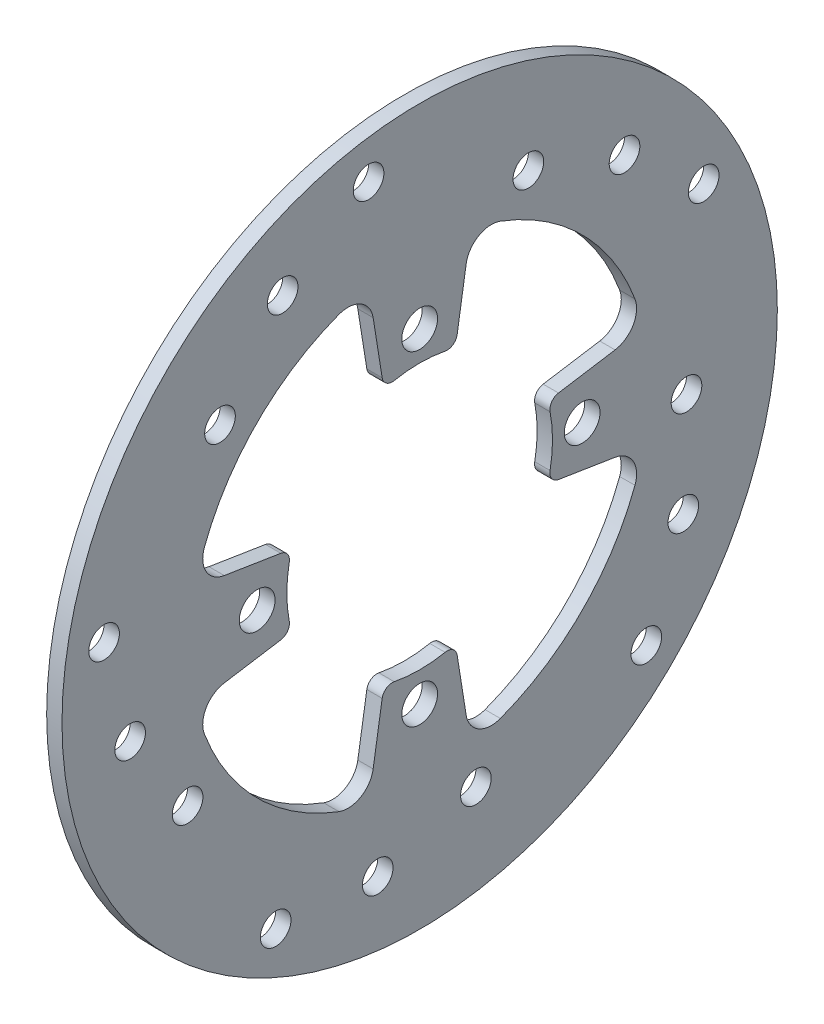
SolidWorks part; units mm, degrees
material "Stainless Steel (ferritic)"
ref_plane "Front Plane" through (0, 0, 0) normal (0, 0, 1) x (1, 0, 0)
ref_plane "Top Plane" through (0, 0, 0) normal (0, 1, 0) x (1, 0, 0)
ref_plane "Right Plane" through (0, 0, 0) normal (1, 0, 0) x (0, 0, -1)
sketch "Sketch1" plane through (0, 0, 0) normal (1, 0, 0) x (0, 0, -1)
  circle A0 centre (0, 0) radius 88.9
  dimension "D1" = 177.8
extrude "Boss-Extrude2" add sketch "Sketch1" along normal blind 3.81
sketch "Sketch3" plane through (3.81, 0, 0) normal (1, 0, 0) x (0, 0, -1)
  line L0 (0, 0) -> (0, 89.75) construction
  line L1 (9.3202, 34.5019) -> (11.5604, 48.5665)
  line L2 (34.5019, -9.3202) -> (48.5665, -11.5604)
  line L3 (-11.5604, 48.5665) -> (-9.3202, 34.5019)
  line L4 (48.5665, 11.5604) -> (34.5019, 9.3202)
  line L5 (-9.3202, -34.5019) -> (-11.5604, -48.5665)
  line L6 (11.5604, -48.5665) -> (9.3202, -34.5019)
  line L7 (-34.5019, 9.3202) -> (-48.5665, 11.5604)
  line L8 (-48.5665, -11.5604) -> (-34.5019, -9.3202)
  arc A0 (-20.0603, 53.5136) -> (-53.5136, 20.0603) centre (0, 0) ccw
  arc A1 (6.3253, 32.4085) -> (-6.3253, 32.4085) centre (0, 0) ccw
  arc A2 (9.3202, 34.5019) -> (6.3253, 32.4085) centre (6.8119, 34.9015) cw
  arc A3 (-9.3202, 34.5019) -> (-6.3253, 32.4085) centre (-6.8119, 34.9015) ccw
  arc A4 (11.5604, 48.5665) -> (20.0603, 53.5136) centre (17.8314, 47.5677) cw
  arc A5 (-20.0603, 53.5136) -> (-11.5604, 48.5665) centre (-17.8314, 47.5677) cw
  arc A6 (48.5665, -11.5604) -> (53.5136, -20.0603) centre (47.5677, -17.8314) cw
  arc A7 (34.5019, -9.3202) -> (32.4085, -6.3253) centre (34.9015, -6.8119) cw
  arc A8 (32.4085, -6.3253) -> (32.4085, 6.3253) centre (0, 0) ccw
  arc A9 (34.5019, 9.3202) -> (32.4085, 6.3253) centre (34.9015, 6.8119) ccw
  arc A10 (53.5136, 20.0603) -> (48.5665, 11.5604) centre (47.5677, 17.8314) cw
  arc A11 (-11.5604, -48.5665) -> (-20.0603, -53.5136) centre (-17.8314, -47.5677) cw
  arc A12 (-9.3202, -34.5019) -> (-6.3253, -32.4085) centre (-6.8119, -34.9015) cw
  arc A13 (-6.3253, -32.4085) -> (6.3253, -32.4085) centre (0, 0) ccw
  arc A14 (9.3202, -34.5019) -> (6.3253, -32.4085) centre (6.8119, -34.9015) ccw
  arc A15 (20.0603, -53.5136) -> (11.5604, -48.5665) centre (17.8314, -47.5677) cw
  arc A16 (-48.5665, 11.5604) -> (-53.5136, 20.0603) centre (-47.5677, 17.8314) cw
  arc A17 (-34.5019, 9.3202) -> (-32.4085, 6.3253) centre (-34.9015, 6.8119) cw
  arc A18 (-32.4085, 6.3253) -> (-32.4085, -6.3253) centre (0, 0) ccw
  arc A19 (-34.5019, -9.3202) -> (-32.4085, -6.3253) centre (-34.9015, -6.8119) ccw
  arc A20 (-53.5136, -20.0603) -> (-48.5665, -11.5604) centre (-47.5677, -17.8314) cw
  arc A21 (53.5136, 20.0603) -> (20.0603, 53.5136) centre (0, 0) ccw
  arc A22 (20.0603, -53.5136) -> (53.5136, -20.0603) centre (0, 0) ccw
  arc A23 (-53.5136, -20.0603) -> (-20.0603, -53.5136) centre (0, 0) ccw
  point P7 (8.89, 31.8008)
  point P12 (-8.89, 31.8008)
  point P15 (12.7, 55.721)
  point P18 (-12.7, 55.721)
  point P58 (0, 0)
  dimension "D1" = 8.89
  dimension "D2" = 114.3
  dimension "D4" = 66.04
  dimension "D3" = 12.7
  dimension "D5" = 2.54
  dimension "D6" = 6.35
  dimension "D7" = 4
extrude "Cut-Extrude1" cut sketch "Sketch3" against normal through all
sketch "Sketch4" plane through (0, 0, 0) normal (-1, 0, 0) x (0, 0, 1)
  circle A0 centre (0, 40.386) radius 4.445
  arc A1 (6.3253, 32.4085) -> (-6.3253, 32.4085) centre (0, 0) ccw construction
  circle A2 centre (40.386, 0) radius 4.445
  circle A3 centre (0, -40.386) radius 4.445
  circle A4 centre (-40.386, 0) radius 4.445
  point P15 (0, 0)
  dimension "D1" = 8.89
  dimension "D2" = 40.386
  dimension "D3" = 4
extrude "Cut-Extrude2" cut sketch "Sketch4" against normal through all
sketch "Sketch5" plane through (3.81, 0, 0) normal (1, 0, 0) x (0, 0, -1)
  circle A0 centre (-12.7, 78.3524) radius 3.81
  circle A1 centre (-34.054, 64.5986) radius 3.81
  circle A2 centre (-49.6244, 44.5306) radius 3.81
  circle A3 centre (0, 0) radius 88.9 construction
  circle A4 centre (0, 40.386) radius 4.445 construction
  circle A5 centre (70.5931, 36.2906) radius 3.81
  circle A6 centre (50.9136, 52.3493) radius 3.81
  circle A7 centre (27.0164, 60.9563) radius 3.81
  circle A8 centre (56.3289, -55.9236) radius 3.81
  circle A9 centre (65.5203, -32.2449) radius 3.81
  circle A10 centre (66.3214, -6.8576) radius 3.81
  circle A11 centre (-35.7799, -70.8533) radius 3.81
  circle A12 centre (-10.4199, -72.2778) radius 3.81
  circle A13 centre (13.9725, -65.1945) radius 3.81
  circle A14 centre (-78.4421, 12.1338) radius 3.81
  circle A15 centre (-71.9602, -12.4252) radius 3.81
  circle A16 centre (-57.6859, -33.4349) radius 3.81
  point P38 (0, 0)
  dimension "D1" = 7.62
  dimension "D2" = 7.62
  dimension "D3" = 7.62
  dimension "D4" = 79.375
  dimension "D5" = 73.025
  dimension "D6" = 66.675
  dimension "D7" = 25.4
  dimension "D8" = 25.4
  dimension "D9" = 12.7
  dimension "D10" = 5
extrude "Cut-Extrude3" cut sketch "Sketch5" against normal through all
